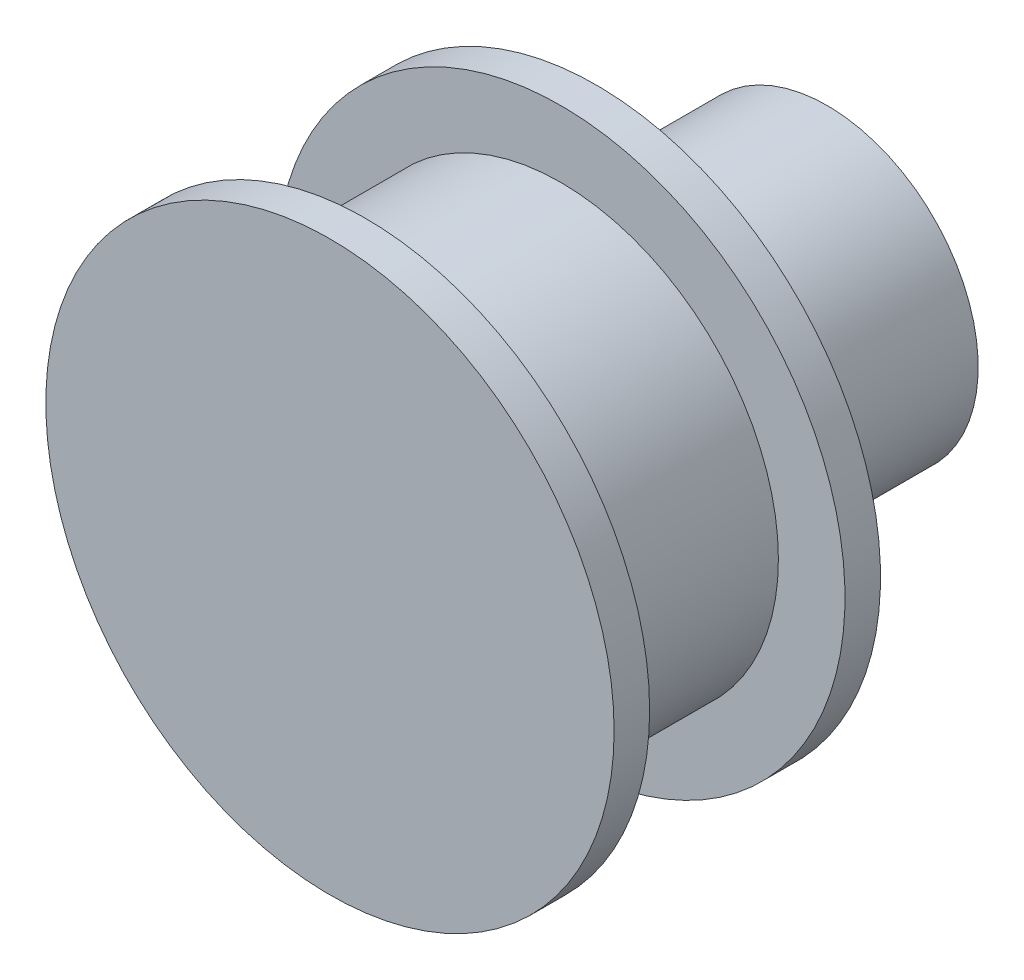
SolidWorks part; units mm, degrees
ref_plane "Front Plane" through (0, 0, 0) normal (0, 0, 1) x (1, 0, 0)
ref_plane "Top Plane" through (0, 0, 0) normal (0, 1, 0) x (1, 0, 0)
ref_plane "Right Plane" through (0, 0, 0) normal (1, 0, 0) x (0, 0, -1)
sketch "Sketch1" plane through (0, 0, 0) normal (0, 0, 1) x (1, 0, 0)
  circle A0 centre (0, 0) radius 12.25
  dimension "D1" = 24.5
extrude "Boss-Extrude1" add sketch "Sketch1" along normal blind 11
sketch "Sketch2" plane through (0, 0, 0) normal (0, 0, -1) x (-1, 0, 0)
  circle A2 centre (0, 0) radius 16
  dimension "D1" = 32
extrude "Boss-Extrude2" add sketch "Sketch2" along normal blind 2
sketch "Sketch3" plane through (0, 0, 11) normal (0, 0, 1) x (1, 0, 0)
  circle A0 centre (0, 0) radius 16
  dimension "D1" = 32
sketch "Sketch4" plane through (0, 0, -2) normal (0, 0, -1) x (-1, 0, 0)
  circle A0 centre (0, 0) radius 10
  dimension "D1" = 20
extrude "Boss-Extrude4" add sketch "Sketch4" along normal blind 1
sketch "Sketch5" plane through (0, 0, -3) normal (0, 0, -1) x (-1, 0, 0)
  circle A0 centre (0, 0) radius 8.5
  dimension "D1" = 17
extrude "Boss-Extrude5" add sketch "Sketch5" along normal blind 12
sketch "Sketch6" plane through (0, 0, -15) normal (0, 0, -1) x (-1, 0, 0)
  circle A0 centre (0, 0) radius 6
  dimension "D1" = 12
extrude "Cut-Extrude1" cut sketch "Sketch6" against normal through all
chamfer "Chamfer1" distance 1 angle 45 1 edges at (-6, 0, -15)
extrude "Boss-Extrude6" add sketch "Sketch3" along normal blind 2
